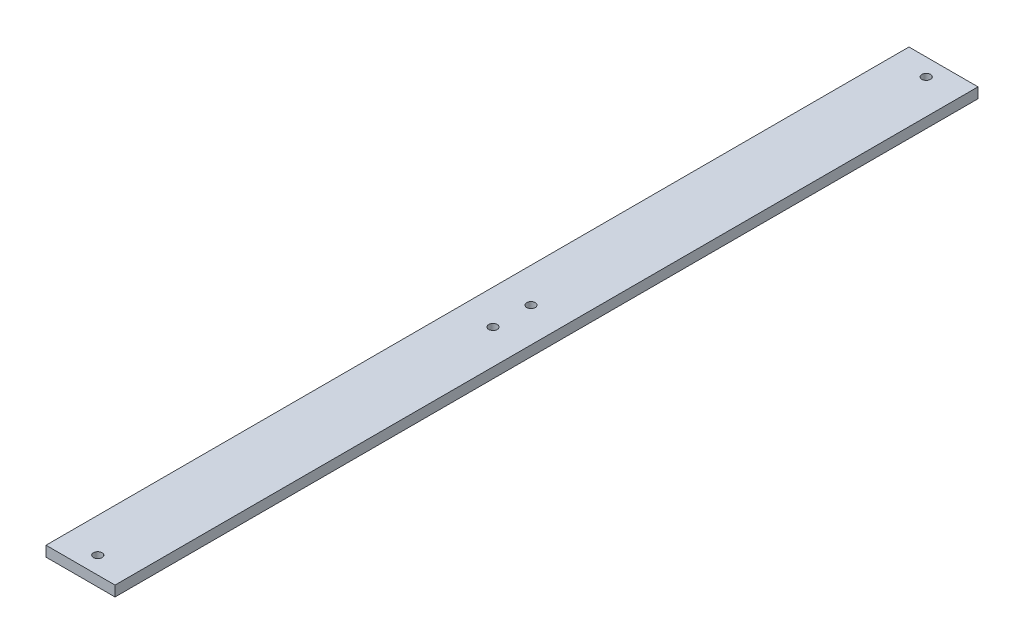
SolidWorks part; units mm, degrees
ref_plane "Front Plane" through (0, 0, 0) normal (0, 0, 1) x (1, 0, 0)
ref_plane "Top Plane" through (0, 0, 0) normal (0, 1, 0) x (1, 0, 0)
ref_plane "Right Plane" through (0, 0, 0) normal (1, 0, 0) x (0, 0, -1)
sketch "Sketch1" plane through (0, 0, 0) normal (0, 0, 1) x (1, 0, 0)
  line L1 (0, 0) -> (40, 0)
  line L2 (0, 0) -> (0, 6)
  line L3 (0, 6) -> (40, 6)
  line L4 (40, 0) -> (40, 6)
  dimension "D1" = 40
  dimension "D2" = 6
extrude "Boss-Extrude1" add sketch "Sketch1" along normal blind 500
sketch "Sketch2" plane through (0, 6, 0) normal (0, 1, 0) x (1, 0, 0)
  line L0 (40, -500) -> (40, 0) construction
  line L1 (40, 0) -> (0, 0) construction
  circle A0 centre (20, -10) radius 2.5
  dimension "D3" = 5
  dimension "D1" = 20
  dimension "D2" = 10
extrude "Cut-Extrude1" cut sketch "Sketch2" against normal blind 10
pattern_linear "LPattern1" count 2 spacing 480 along (0, 0, 1) of "Cut-Extrude1"
sketch "Sketch3" plane through (0, 6, 0) normal (0, 1, 0) x (1, 0, 0)
  line L0 (40, 0) -> (0, 0) construction
  line L1 (40, -500) -> (40, 0) construction
  circle A0 centre (20, -239) radius 2.5
  dimension "D3" = 5
  dimension "D1" = 239
  dimension "D2" = 20
extrude "Cut-Extrude2" cut sketch "Sketch3" against normal blind 10
pattern_linear "LPattern2" count 2 spacing 22 along (0, 0, 1) of "Cut-Extrude2"
